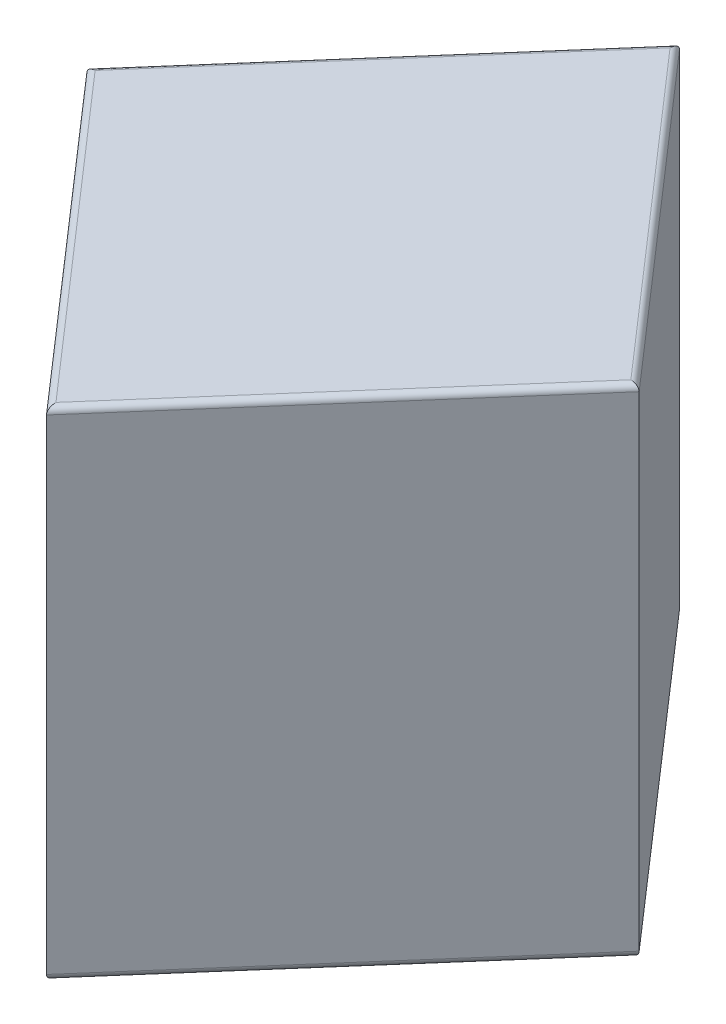
SolidWorks part; units mm, degrees
ref_plane "Front Plane" through (0, 0, 0) normal (1, 0, 0) x (0, 1, 0)
ref_plane "Top Plane" through (0, 0, 0) normal (0, 0, 1) x (0, 1, 0)
ref_plane "Right Plane" through (0, 0, 0) normal (0, 1, 0) x (-1, 0, 0)
sketch "Sketch1" plane through (0, 0, 0) normal (0, 1, 0) x (-1, 0, 0)
  line L0 (22.2286, 0) -> (0, -25.4789)
  line L1 (0, -25.4789) -> (-22.2286, 0)
  line L2 (-22.2286, 0) -> (0, 25.4789)
  line L3 (0, 25.4789) -> (22.2286, 0)
extrude "Boss-Extrude1" add sketch "Sketch1" along normal blind 40
fillet "Fillet1" radius 0.5 8 edges at (-11.1143, 0, 12.7394) (11.1143, 0, 12.7394) (11.1143, 0, -12.7394) (-11.1143, 0, -12.7394) (-11.1143, 40, 12.7394) (11.1143, 40, 12.7394) (11.1143, 40, -12.7394) (-11.1143, 40, -12.7394)
